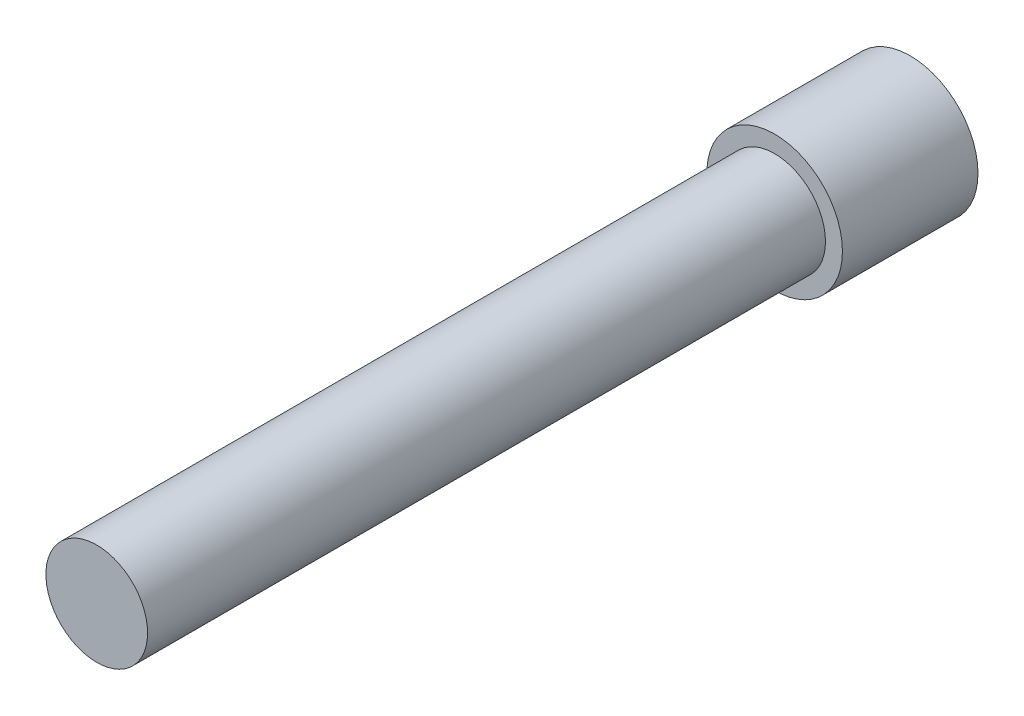
SolidWorks part; units mm, degrees
material "Alloy Steel"
ref_plane "Front Plane" through (0, 0, 0) normal (0, 0, 1) x (1, 0, 0)
ref_plane "Top Plane" through (0, 0, 0) normal (0, 1, 0) x (1, 0, 0)
ref_plane "Right Plane" through (0, 0, 0) normal (1, 0, 0) x (0, 0, -1)
sketch "Sketch1" plane through (0, 0, 0) normal (0, 0, 1) x (1, 0, 0)
  circle A0 centre (0, 0) radius 10
  dimension "D1" = 20
extrude "Boss-Extrude1" add sketch "Sketch1" along normal blind 20
sketch "Sketch2" plane through (0, 0, 20) normal (0, 0, 1) x (1, 0, 0)
  circle A0 centre (0, 0) radius 7.5
  dimension "D1" = 15
extrude "Boss-Extrude2" add sketch "Sketch2" along normal blind 100
